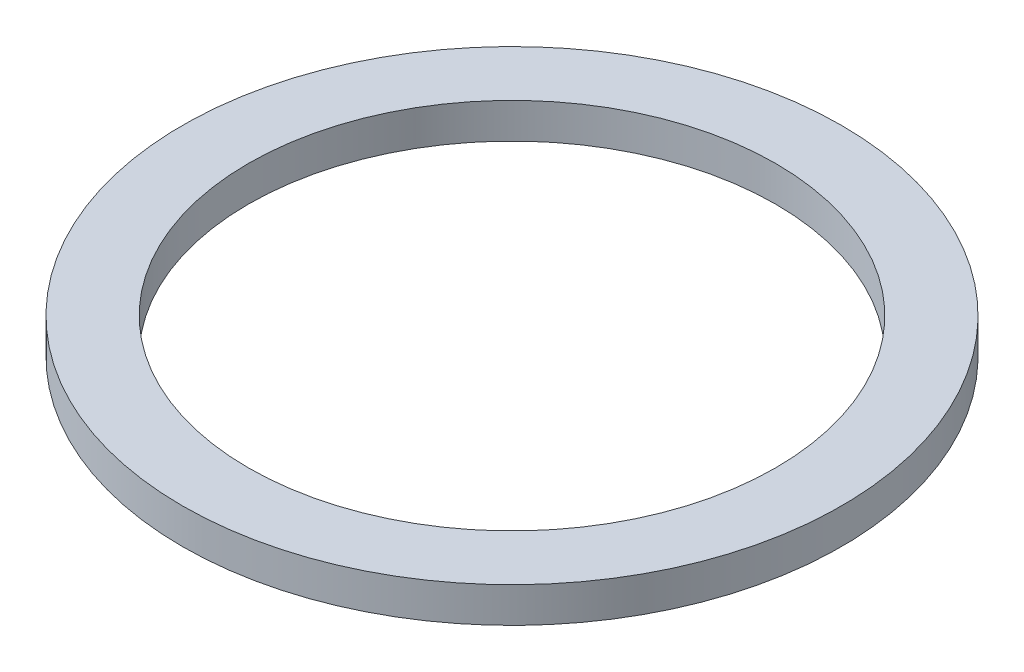
SolidWorks part; units mm, degrees
ref_plane "Front Plane" through (0, 0, 0) normal (0, 0, 1) x (1, 0, 0)
ref_plane "Top Plane" through (0, 0, 0) normal (0, 1, 0) x (1, 0, 0)
ref_plane "Right Plane" through (0, 0, 0) normal (1, 0, 0) x (0, 0, -1)
sketch "Sketch1" plane through (0, 0, 0) normal (0, 1, 0) x (1, 0, 0)
  circle A0 centre (0, 0) radius 40
  circle A1 centre (0, 0) radius 50
  point P3 (0, 0)
  point P4 (60.9674, 0)
  dimension "D1" = 80
  dimension "D2" = 100
extrude "Boss-Extrude1" add sketch "Sketch1" along normal blind 5.3522
